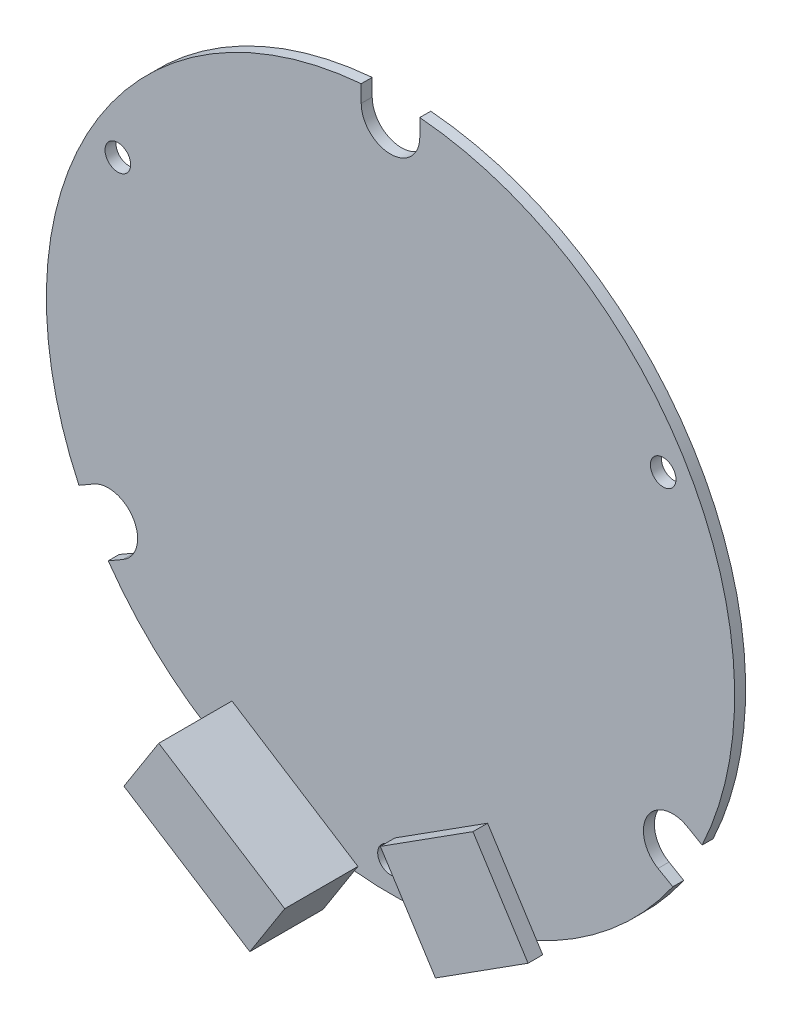
SolidWorks part; units mm, degrees
ref_plane "Alzado" through (0, 0, 0) normal (0, 0, 1) x (1, 0, 0)
ref_plane "Planta" through (0, 0, 0) normal (0, 1, 0) x (1, 0, 0)
ref_plane "Vista lateral" through (0, 0, 0) normal (1, 0, 0) x (0, 0, -1)
sketch "Croquis1" plane through (0, 0, 0) normal (0, 0, 1) x (1, 0, 0)
  line L0 (-3, 44.5) -> (-3, 47.9062) construction
  line L1 (3, 44.5) -> (3, 47.9062) construction
  line L2 (0, 44.5) -> (0, 0) construction
  line L3 (37.0381, -24.8481) -> (39.988, -26.5512) construction
  line L4 (40.0381, -19.6519) -> (42.988, -21.355) construction
  line L5 (-40.0381, -19.6519) -> (-42.988, -21.355) construction
  line L6 (-37.0381, -24.8481) -> (-39.988, -26.5512) construction
  line L7 (0, 0) -> (0, 44.5) construction
  line L8 (0, 0) -> (38.5381, -22.25) construction
  line L9 (-4, 44.5) -> (-4, 46.8295)
  line L10 (-40.5381, -18.7859) -> (-42.5555, -19.9506)
  line L11 (-36.5381, -25.7141) -> (-38.5555, -26.8788)
  line L12 (36.5381, -25.7141) -> (38.5555, -26.8788)
  line L13 (40.5381, -18.7859) -> (42.5555, -19.9506)
  line L14 (4, 44.5) -> (4, 46.8295)
  line L15 (1, 44.5) -> (1, 0)
  arc A0 (-39.988, -26.5512) -> (39.988, -26.5512) centre (0, 0) ccw construction
  arc A1 (-3, 44.5) -> (3, 44.5) centre (0, 44.5) ccw construction
  arc A2 (40.0381, -19.6519) -> (37.0381, -24.8481) centre (38.5381, -22.25) ccw construction
  arc A3 (-37.0381, -24.8481) -> (-40.0381, -19.6519) centre (-38.5381, -22.25) ccw construction
  arc A4 (42.988, -21.355) -> (3, 47.9062) centre (0, 0) ccw construction
  arc A5 (-3, 47.9062) -> (-42.988, -21.355) centre (0, 0) ccw construction
  arc A6 (-4, 46.8295) -> (-42.5555, -19.9506) centre (0, 0) ccw
  arc A7 (-36.5381, -25.7141) -> (-40.5381, -18.7859) centre (-38.5381, -22.25) ccw
  arc A8 (-38.5555, -26.8788) -> (38.5555, -26.8788) centre (0, 0) ccw
  arc A9 (40.5381, -18.7859) -> (36.5381, -25.7141) centre (38.5381, -22.25) ccw
  arc A10 (42.5555, -19.9506) -> (4, 46.8295) centre (0, 0) ccw
  arc A11 (-4, 44.5) -> (4, 44.5) centre (0, 44.5) ccw
  dimension "D1" = 96
  dimension "D2" = 44.5
  dimension "D3" = 6
  dimension "D4" = 3
  dimension "D5" = 120
  dimension "D6" = 1
extrude "Saliente-Extruir1" add sketch "Croquis1" along normal blind 1.5
sketch "Croquis2" plane through (0, 0, 1.5) normal (0, 0, 1) x (1, 0, 0)
  line L0 (0, 0) -> (-37.2391, 21.5) construction
  line L1 (0, 0) -> (0, 40.5) construction
  line L2 (0, 0) -> (-37.2391, 21.5) construction
  line L3 (0, 0) -> (37.2391, 21.5) construction
  circle A0 centre (-37.2391, 21.5) radius 1.75
  arc A1 (-4, 44.5) -> (4, 44.5) centre (0, 44.5) ccw construction
  circle A2 centre (37.2391, 21.5) radius 1.75
  circle A3 centre (0, -43) radius 1.75
  dimension "D1" = 3.5
  dimension "D2" = 60
  dimension "D3" = 43
  dimension "D5" = 120
  dimension "D4" = 3
extrude "Cortar-Extruir1" cut sketch "Croquis2" against normal blind 1.5
sketch "Croquis3" plane through (0, 0, 1.5) normal (0, 0, 1) x (1, 0, 0)
  line L0 (8.9358, -34.0382) -> (16.4642, -45.8418) construction
  line L1 (0, 0) -> (0, 40.5) construction
  line L2 (19.0233, -35.9069) -> (6.3767, -43.9731) construction
  line L3 (15.2591, -30.0052) -> (22.7875, -41.8087)
  line L4 (15.2591, -30.0052) -> (2.6125, -38.0713)
  line L5 (22.7875, -41.8087) -> (10.1409, -49.8748)
  line L6 (2.6125, -38.0713) -> (10.1409, -49.8748)
  line L7 (0, 0) -> (26.6343, 0) construction
  line L12 (-4, 44.5) -> (-4, 46.8295)
  line L13 (-42.5555, -19.9506) -> (-40.5381, -18.7859)
  line L14 (-36.5381, -25.7141) -> (-38.5555, -26.8788)
  line L15 (38.5555, -26.8788) -> (36.5381, -25.7141)
  line L16 (40.5381, -18.7859) -> (42.5555, -19.9506)
  line L17 (4, 46.8295) -> (4, 44.5)
  line L18 (-4, 44.5) -> (-4, 46.8295) construction
  line L19 (-42.5555, -19.9506) -> (-40.5381, -18.7859) construction
  line L20 (-36.5381, -25.7141) -> (-38.5555, -26.8788) construction
  line L21 (38.5555, -26.8788) -> (36.5381, -25.7141) construction
  line L22 (40.5381, -18.7859) -> (42.5555, -19.9506) construction
  line L23 (4, 46.8295) -> (4, 44.5) construction
  arc A1 (-4, 44.5) -> (4, 44.5) centre (0, 44.5) ccw construction
  arc A8 (-4, 44.5) -> (4, 44.5) centre (0, 44.5) ccw
  arc A9 (-4, 46.8295) -> (-42.5555, -19.9506) centre (0, 0) ccw
  arc A10 (-36.5381, -25.7141) -> (-40.5381, -18.7859) centre (-38.5381, -22.25) ccw
  arc A11 (-38.5555, -26.8788) -> (38.5555, -26.8788) centre (0, 0) ccw
  arc A12 (40.5381, -18.7859) -> (36.5381, -25.7141) centre (38.5381, -22.25) ccw
  arc A13 (42.5555, -19.9506) -> (4, 46.8295) centre (0, 0) ccw
  arc A14 (-4, 44.5) -> (4, 44.5) centre (0, 44.5) ccw construction
  arc A15 (-4, 46.8295) -> (-42.5555, -19.9506) centre (0, 0) ccw construction
  arc A16 (-36.5381, -25.7141) -> (-40.5381, -18.7859) centre (-38.5381, -22.25) ccw construction
  arc A17 (-38.5555, -26.8788) -> (38.5555, -26.8788) centre (0, 0) ccw construction
  arc A18 (40.5381, -18.7859) -> (36.5381, -25.7141) centre (38.5381, -22.25) ccw construction
  arc A19 (42.5555, -19.9506) -> (4, 46.8295) centre (0, 0) ccw construction
  point P6 (12.7, -39.94)
  point P12 (6.3767, -43.9731)
  dimension "D1" = 32.53
  dimension "D2" = 12.7
  dimension "D3" = 15
  dimension "D4" = 14
  dimension "D6" = 39.94
  dimension "D5" = 0
extrude "Saliente-Extruir2" add sketch "Croquis3" along normal blind 2 from offset 2 separate body
sketch "Croquis4" plane through (0, 0, 1.5) normal (0, 0, 1) x (1, 0, 0)
  line L0 (-26.4091, -42.465) -> (-9.2104, -53.4362)
  line L1 (-26.4091, -42.465) -> (-21.6496, -35.0038)
  line L2 (-9.2104, -53.4362) -> (-4.4509, -45.975)
  line L3 (-21.6496, -35.0038) -> (-4.4509, -45.975)
  line L4 (-26.4091, -42.465) -> (-4.4509, -45.975) construction
  line L5 (-9.2104, -53.4362) -> (-21.6496, -35.0038) construction
  line L6 (0, 0) -> (-21.3963, 0) construction
  point P1 (-15.43, -44.22)
  dimension "D1" = 8.85
  dimension "D2" = 20.4
  dimension "D3" = 32.534
  dimension "D4" = 44.22
  dimension "D5" = 15.43
extrude "Saliente-Extruir3" add sketch "Croquis4" along normal blind 10
